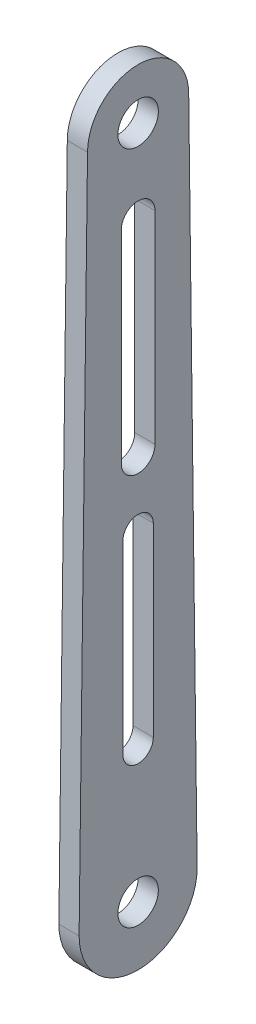
SolidWorks part; units mm, degrees
ref_plane "Front Plane" through (0, 0, 0) normal (0, 0, 1) x (1, 0, 0)
ref_plane "Top Plane" through (0, 0, 0) normal (0, 1, 0) x (1, 0, 0)
ref_plane "Right Plane" through (0, 0, 0) normal (1, 0, 0) x (0, 0, -1)
sketch "草图1" plane through (0, 0, 0) normal (1, 0, 0) x (0, 0, -1)
  line L0 (0, 0) -> (0, -200) construction
  line L1 (15, 0) -> (17.5, -200)
  line L2 (-17.5, -200) -> (-15, 0)
  arc A0 (15, 0) -> (-15, 0) centre (0, 0) ccw
  circle A1 centre (0, 0) radius 6
  arc A2 (-17.5, -200) -> (17.5, -200) centre (0, -200) ccw
  circle A3 centre (0, -200) radius 6
  dimension "D1" = 30
  dimension "D2" = 12
  dimension "D4" = 35
  dimension "D5" = 12
  dimension "D3" = 200
extrude "凸台-拉伸1" add sketch "草图1" along normal blind 6
sketch "草图2" plane through (6, 0, 0) normal (1, 0, 0) x (0, 0, -1)
  line L0 (0, -25) -> (0, -85) construction
  line L2 (5, -25) -> (5, -85)
  line L3 (-5, -25) -> (-5, -85)
  line L4 (0, -105) -> (0, -160) construction
  line L5 (4.5, -105) -> (4.5, -160)
  line L6 (-4.5, -105) -> (-4.5, -160)
  arc A0 (5, -25) -> (-5, -25) centre (0, -25) ccw
  arc A1 (-5, -85) -> (5, -85) centre (0, -85) ccw
  arc A2 (4.5, -105) -> (-4.5, -105) centre (0, -105) ccw
  arc A3 (-4.5, -160) -> (4.5, -160) centre (0, -160) ccw
  point P5 (0, -55)
  point P10 (0, -132.5)
  dimension "D1" = 25
  dimension "D3" = 20
  dimension "D2" = 60
  dimension "D4" = 55
extrude "切除-拉伸1" cut sketch "草图2" against normal blind 10
